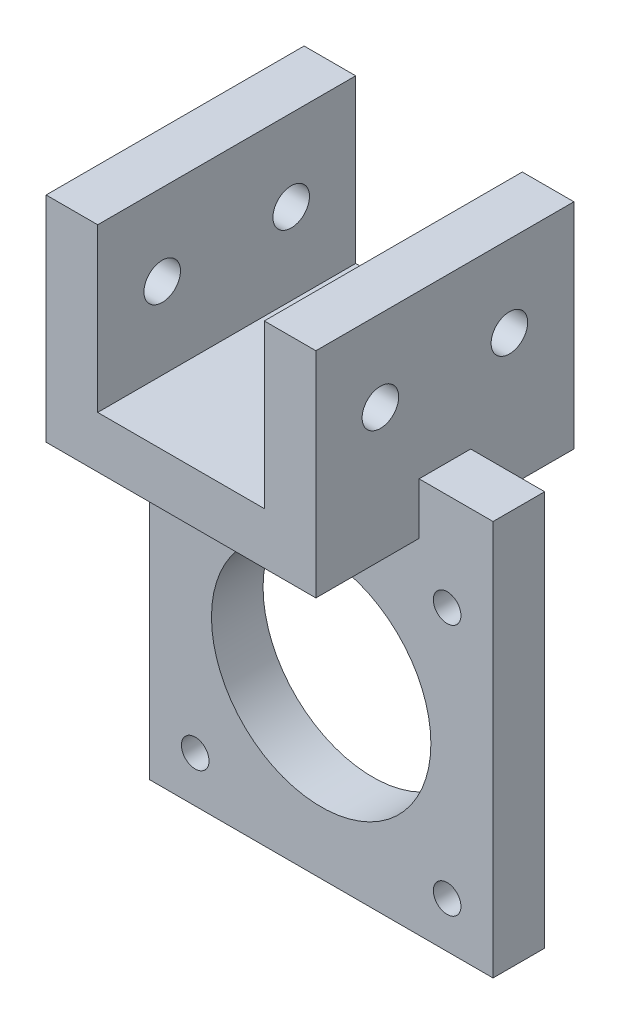
SolidWorks part; units mm, degrees
ref_plane "Front Plane" through (0, 0, 0) normal (0, 0, 1) x (1, 0, 0)
ref_plane "Top Plane" through (0, 0, 0) normal (0, 1, 0) x (1, 0, 0)
ref_plane "Right Plane" through (0, 0, 0) normal (1, 0, 0) x (0, 0, -1)
sketch "Sketch6" plane through (0, 0, 0) normal (0, 0, 1) x (1, 0, 0)
  line L1 (-21.15, -21.15) -> (21.15, -21.15)
  line L2 (-21.15, -21.15) -> (-21.15, 21.15)
  line L3 (-21.15, 21.15) -> (21.15, 21.15)
  line L4 (21.15, -21.15) -> (21.15, 21.15)
  line L5 (-21.15, -21.15) -> (21.15, 21.15) construction
  line L6 (-21.15, 21.15) -> (21.15, -21.15) construction
  line L7 (-15.5, -15.5) -> (15.5, -15.5)
  line L8 (-15.5, -15.5) -> (-15.5, 15.5)
  line L9 (-15.5, 15.5) -> (15.5, 15.5)
  line L10 (15.5, -15.5) -> (15.5, 15.5)
  line L11 (-15.5, -15.5) -> (15.5, 15.5) construction
  line L12 (-15.5, 15.5) -> (15.5, -15.5) construction
  circle A0 centre (-15.5, 15.5) radius 1.7
  circle A1 centre (15.5, 15.5) radius 1.7
  circle A2 centre (15.5, -15.5) radius 1.7
  circle A3 centre (-15.5, -15.5) radius 1.7
  circle A4 centre (0, 0) radius 13.5
  point P0 (0, 0)
  point P6 (0, 0)
  dimension "D4" = 3.4
  dimension "D5" = 3.4
  dimension "D6" = 3.4
  dimension "D7" = 3.4
  dimension "D8" = 27
  dimension "D1" = 42.3
  dimension "D2" = 42.3
  dimension "D3" = 31
extrude "Boss-Extrude4" add sketch "Sketch6" along normal blind 6.35 contours A3 L7 A2 L10 A1 L9 A0 L8 A4 | L1 L4 L3 L2 A3 L8 A0 L9 A1 L10 A2 L7
sketch "Sketch7" plane through (0, 21.15, 0) normal (0, 1, 0) x (1, 0, 0)
  line L1 (21.15, 6.35) -> (-21.15, 6.35)
  line L2 (21.15, 6.35) -> (21.15, -6.35)
  line L3 (21.15, -6.35) -> (-21.15, -6.35)
  line L4 (-21.15, 6.35) -> (-21.15, -6.35)
  line L5 (21.15, 6.35) -> (-21.15, -6.35) construction
  line L6 (21.15, -6.35) -> (-21.15, 6.35) construction
  line L7 (-21.15, 0) -> (21.15, 0)
  line M5 (21.15, 0) -> (-21.15, 0)
  line M6 (-21.15, 0) -> (-21.15, -6.35)
  line M7 (-21.15, -6.35) -> (21.15, -6.35)
  line M8 (21.15, -6.35) -> (21.15, 0)
extrude "Boss-Extrude5" add sketch "Sketch7" along normal blind 6.35 contours M8 M5 M6 M7
sketch "Sketch9" plane through (0, 27.5, 0) normal (0, 1, 0) x (1, 0, 0)
  line L5 (-21.15, -6.35) -> (21.15, -6.35) construction
  line L6 (-21.15, 0) -> (-14.8, 0)
  line L7 (-21.15, 0) -> (-21.15, -6.35)
  line L8 (-21.15, -6.35) -> (-14.8, -6.35)
  line L9 (-14.8, 0) -> (-14.8, -6.35)
  line L10 (21.15, 0) -> (-21.15, 0) construction
  line L11 (12.05, -6.35) -> (5.7, -6.35)
  line L12 (12.05, -6.35) -> (12.05, 0)
  line L13 (12.05, 0) -> (5.7, 0)
  line L14 (5.7, -6.35) -> (5.7, 0)
  dimension "D1" = 6.35
  dimension "D2" = 6.35
  dimension "D3" = 20.5
extrude "Boss-Extrude7" add sketch "Sketch9" along normal blind 20
sketch "Sketch11" plane through (0, 0, 0) normal (0, 0, -1) x (-1, 0, 0)
  line L0 (-12.05, 47.5) -> (-12.05, 27.5)
  line L1 (-12.05, 27.5) -> (-12.05, 21.15)
  line L2 (-12.05, 21.15) -> (21.15, 21.15)
  line L3 (21.15, -21.15) -> (21.15, 47.5) construction
  line L4 (21.15, 21.15) -> (21.15, 47.5)
  line L5 (21.15, 47.5) -> (14.8, 47.5)
  line L6 (14.8, 47.5) -> (14.8, 27.5)
  line L7 (14.8, 27.5) -> (-5.7, 27.5)
  line L8 (-5.7, 27.5) -> (-5.7, 47.5)
  line L9 (-12.05, 47.5) -> (-5.7, 47.5)
  dimension "D1" = 6.35
extrude "Boss-Extrude9" add sketch "Sketch11" along normal blind 12.7 and the other way blind 19.05
sketch "Sketch12" plane through (12.05, 0, 0) normal (1, 0, 0) x (0, 0, -1)
  line L0 (-19.05, 47.5) -> (-19.05, 21.15) construction
  line L1 (12.7, 47.5) -> (-19.05, 47.5)
  line L2 (12.7, 47.5) -> (12.7, 27.5)
  line L3 (12.7, 27.5) -> (-19.05, 27.5)
  line L4 (-19.05, 47.5) -> (-19.05, 27.5)
  line L5 (-3.175, 37.5) -> (-19.05, 37.5)
  line L6 (-3.175, 47.5) -> (-3.175, 27.5)
  line L7 (-3.175, 37.5) -> (12.7, 37.5)
  circle A0 centre (4.7625, 37.5) radius 2.25
  circle A1 centre (-11.1125, 37.5) radius 2.25
  dimension "D2" = 4.5
  dimension "D3" = 4.5
  dimension "D1" = 20
extrude "Cut-Extrude3" cut sketch "Sketch12" against normal through all contours L7 A0 | L7 A0 | L5 A1 | L5 A1
